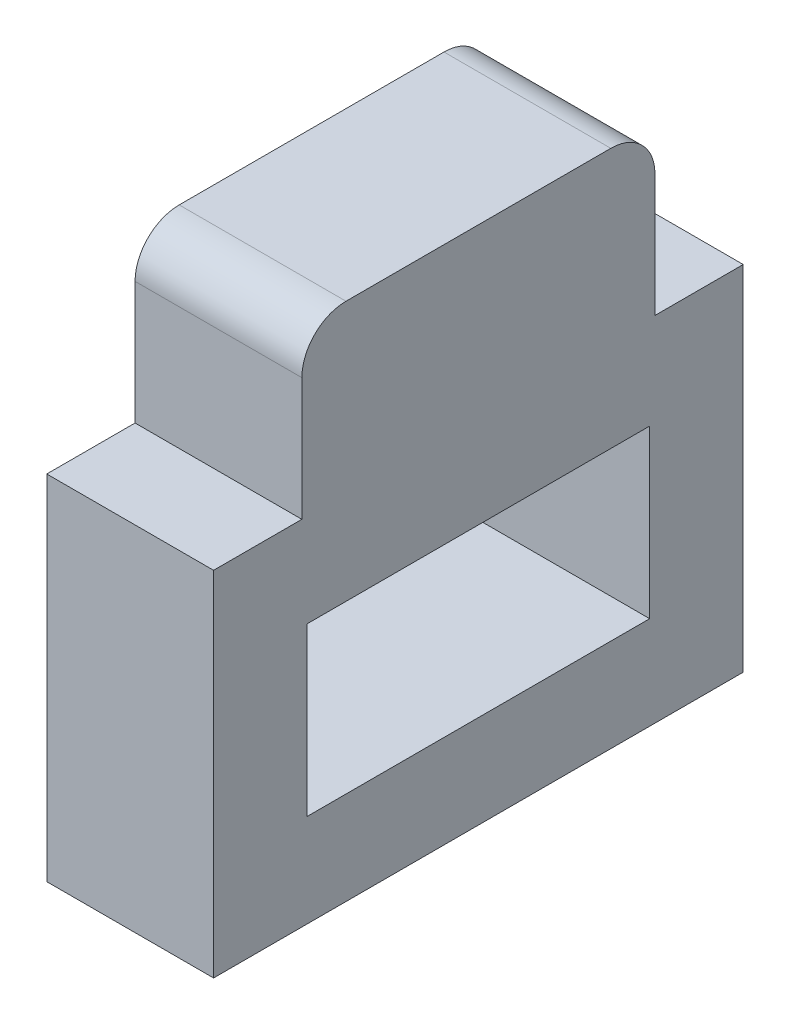
SolidWorks part; units mm, degrees
ref_plane "Front Plane" through (0, 0, 0) normal (0, 0, 1) x (1, 0, 0)
ref_plane "Top Plane" through (0, 0, 0) normal (0, 1, 0) x (1, 0, 0)
ref_plane "Right Plane" through (0, 0, 0) normal (1, 0, 0) x (0, 0, -1)
sketch "Sketch1" plane through (0, 0, 0) normal (1, 0, 0) x (0, 0, -1)
  line L1 (9.525, -6.35) -> (-9.525, -6.35)
  line L2 (9.525, -6.35) -> (9.525, 6.35)
  line L3 (9.525, 6.35) -> (-9.525, 6.35)
  line L4 (-9.525, -6.35) -> (-9.525, 6.35)
  line L5 (9.525, -6.35) -> (-9.525, 6.35) construction
  line L6 (9.525, 6.35) -> (-9.525, -6.35) construction
  point P0 (0, 0)
  dimension "D1" = 12.7
  dimension "D2" = 19.05
extrude "Boss-Extrude1" add sketch "Sketch1" along normal mid plane 6
sketch "Sketch2" plane through (0, 6.35, 0) normal (0, 1, 0) x (1, 0, 0)
  line L0 (3, 9.525) -> (3, -9.525) construction
  line L1 (-3, -6.35) -> (3, -6.35)
  line L2 (-3, -6.35) -> (-3, 6.35)
  line L3 (-3, 6.35) -> (3, 6.35)
  line L4 (3, -6.35) -> (3, 6.35)
  line L5 (-3, -6.35) -> (3, 6.35) construction
  line L6 (-3, 6.35) -> (3, -6.35) construction
  point P0 (0, 0)
  dimension "D1" = 12.7
extrude "Boss-Extrude2" add sketch "Sketch2" along normal blind 6 contours L3 L4 L1 L2
sketch "Sketch3" plane through (3, 0, 0) normal (1, 0, 0) x (0, 0, -1)
  line L5 (6.1595, -3) -> (-6.1595, -3)
  line L6 (6.1595, -3) -> (6.1595, 3)
  line L7 (6.1595, 3) -> (-6.1595, 3)
  line L8 (-6.1595, -3) -> (-6.1595, 3)
  line L9 (6.1595, -3) -> (-6.1595, 3) construction
  line L10 (6.1595, 3) -> (-6.1595, -3) construction
  point P0 (0, 0)
  dimension "D1" = 6
  dimension "D2" = 12.319
extrude "Cut-Extrude1" cut sketch "Sketch3" against normal through all
fillet "Fillet1" radius 1.5875 2 edges at (0, 12.35, -6.35) (0, 12.35, 6.35)
equation "\"D1@Sketch3\"=6mm"
